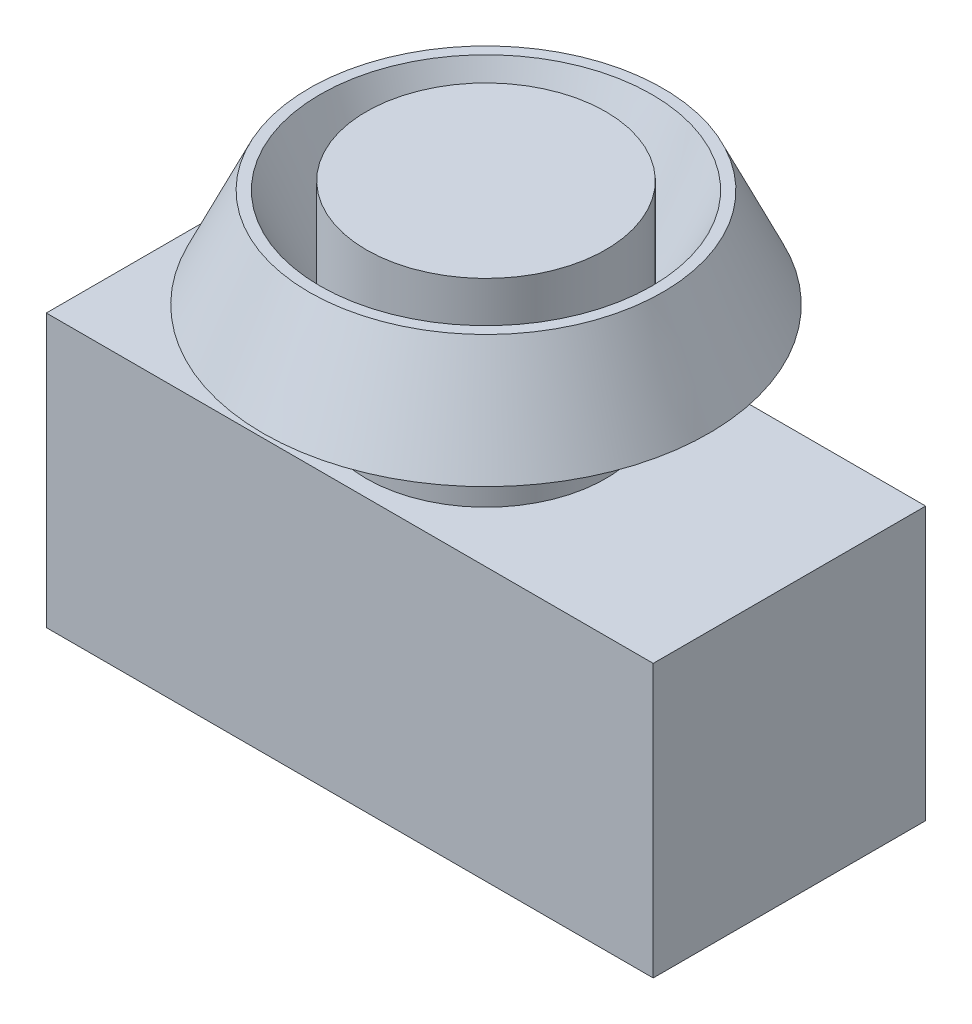
SolidWorks part; units mm, degrees
ref_plane "Front Plane" through (0, 0, 0) normal (0, 0, 1) x (1, 0, 0)
ref_plane "Top Plane" through (0, 0, 0) normal (0, 1, 0) x (1, 0, 0)
ref_plane "Right Plane" through (0, 0, 0) normal (1, 0, 0) x (0, 0, -1)
sketch "Sketch1" plane through (0, 0, 0) normal (0, 0, 1) x (1, 0, 0)
  line L1 (-14.5852, 6.5484) -> (14.5852, 6.5484)
  line L2 (-14.5852, 6.5484) -> (-14.5852, -6.5484)
  line L3 (-14.5852, -6.5484) -> (14.5852, -6.5484)
  line L4 (14.5852, 6.5484) -> (14.5852, -6.5484)
  line L5 (0, -6.5484) -> (0, 6.5484) construction
  line L6 (-14.5852, 0) -> (14.5852, 0) construction
  point P0 (0, 0)
  dimension "D1" = 13.0969
  dimension "D2" = 29.1703
extrude "Boss-Extrude1" add sketch "Sketch1" along normal blind 13.0969
sketch "Sketch2" plane through (0, 6.5484, 0) normal (0, 1, 0) x (1, 0, 0)
  line L0 (-14.5852, 0) -> (14.5852, -13.0969) construction
  circle A0 centre (0, -6.5484) radius 5.7547
  point P5 (0, -6.5484)
  dimension "D1" = 11.5094
extrude "Boss-Extrude2" add sketch "Sketch2" along normal blind 9.525
sketch "Sketch3" plane through (0, 16.0734, 0) normal (0, 1, 0) x (1, 0, 0)
  circle A0 centre (0, -6.5484) radius 10.7156
  circle A1 centre (0, -6.5484) radius 5.7547 construction
  circle A2 centre (0, -6.5484) radius 5.7547
  dimension "D1" = 21.4312
extrude "Boss-Extrude3" add sketch "Sketch3" along normal blind 4.7625 draft 25 from offset 5.1594
